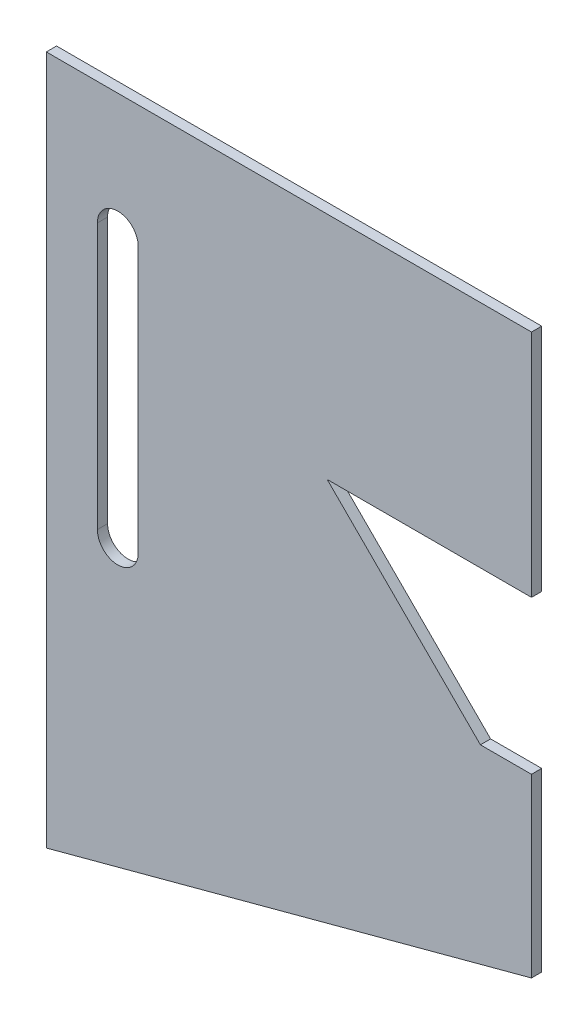
SolidWorks part; units mm, degrees
ref_plane "Ebene vorne" through (0, 0, 0) normal (0, 0, 1) x (1, 0, 0)
ref_plane "Ebene oben" through (0, 0, 0) normal (0, 1, 0) x (1, 0, 0)
ref_plane "Ebene rechts" through (0, 0, 0) normal (1, 0, 0) x (0, 0, -1)
sketch "Skizze2" plane through (0, 0, 0) normal (0, 0, 1) x (1, 0, 0)
  line L0 (0, 0) -> (95, 25.4552)
  line L1 (95, 25.4552) -> (95, 60)
  line L2 (95, 60) -> (85, 60)
  line L3 (85, 60) -> (55, 90)
  line L4 (55, 90) -> (95, 90)
  line L5 (95, 90) -> (95, 135)
  line L6 (95, 135) -> (0, 135)
  line L7 (0, 135) -> (0, 0)
  line L8 (14, 111) -> (14, 59) construction
  line L9 (18, 111) -> (18, 59)
  line L10 (10, 111) -> (10, 59)
  arc A0 (18, 111) -> (10, 111) centre (14, 111) ccw
  arc A1 (10, 59) -> (18, 59) centre (14, 59) ccw
  point P11 (14, 85)
  dimension "D11" = 52
  dimension "D1" = 135
  dimension "D2" = 95
  dimension "D3" = 10
  dimension "D4" = 75
  dimension "D5" = 45
  dimension "D6" = 40
  dimension "D7" = 45
  dimension "D8" = 95
  dimension "D9" = 30
  dimension "D10" = 8
  dimension "D12" = 24
extrude "Aufsatz-Linear austragen1" add sketch "Skizze2" along normal blind 2
